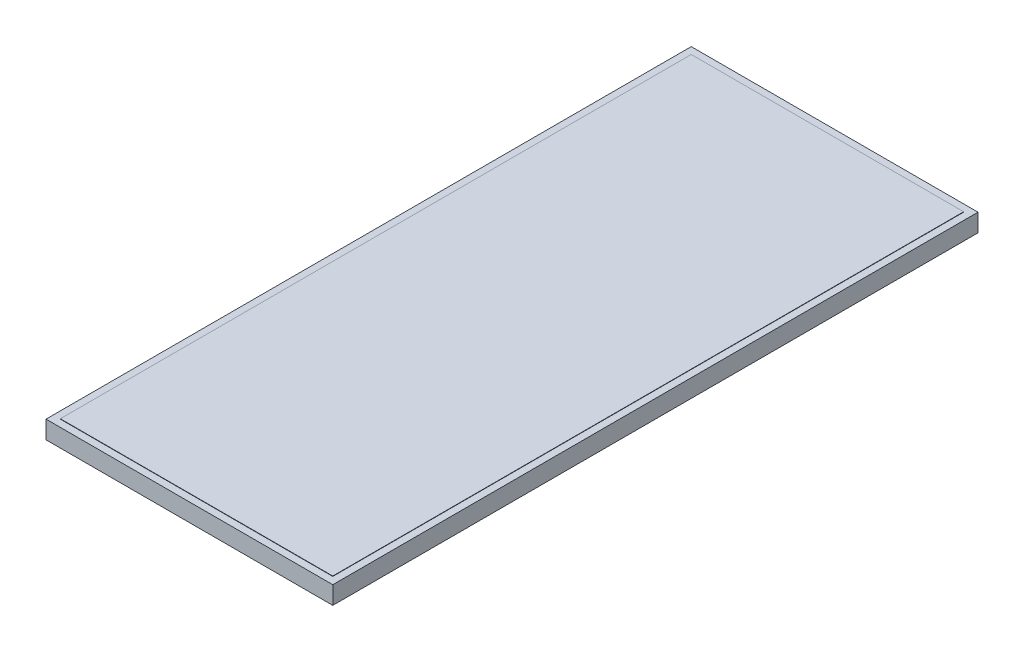
SolidWorks part; units mm, degrees
material "Cedar"
ref_plane "Front Plane" through (0, 0, 0) normal (0, 0, 1) x (1, 0, 0)
ref_plane "Top Plane" through (0, 0, 0) normal (0, 1, 0) x (1, 0, 0)
ref_plane "Right Plane" through (0, 0, 0) normal (1, 0, 0) x (0, 0, -1)
sketch "Sketch1" plane through (0, 0, 0) normal (0, 1, 0) x (1, 0, 0)
  line L1 (0, 0) -> (800, 0)
  line L2 (0, 0) -> (0, 1800)
  line L3 (0, 1800) -> (800, 1800)
  line L4 (800, 0) -> (800, 1800)
  dimension "D1" = 1800
  dimension "D2" = 800
extrude "Boss-Extrude1" add sketch "Sketch1" along normal blind 50
sketch "Sketch5" plane through (0, 50, 0) normal (0, 1, 0) x (1, 0, 0)
  line L8 (20, 1780) -> (20, 20)
  line L9 (20, 20) -> (780, 20)
  line L10 (780, 20) -> (780, 1780)
  line L11 (780, 1780) -> (20, 1780)
  line L12 (20, 1780) -> (20, 20)
  line L13 (20, 20) -> (780, 20)
  line L14 (780, 20) -> (780, 1780)
  line L15 (780, 1780) -> (20, 1780)
  dimension "D1" = 20
extrude "Boss-Extrude2" add sketch "Sketch5" along normal blind 1
